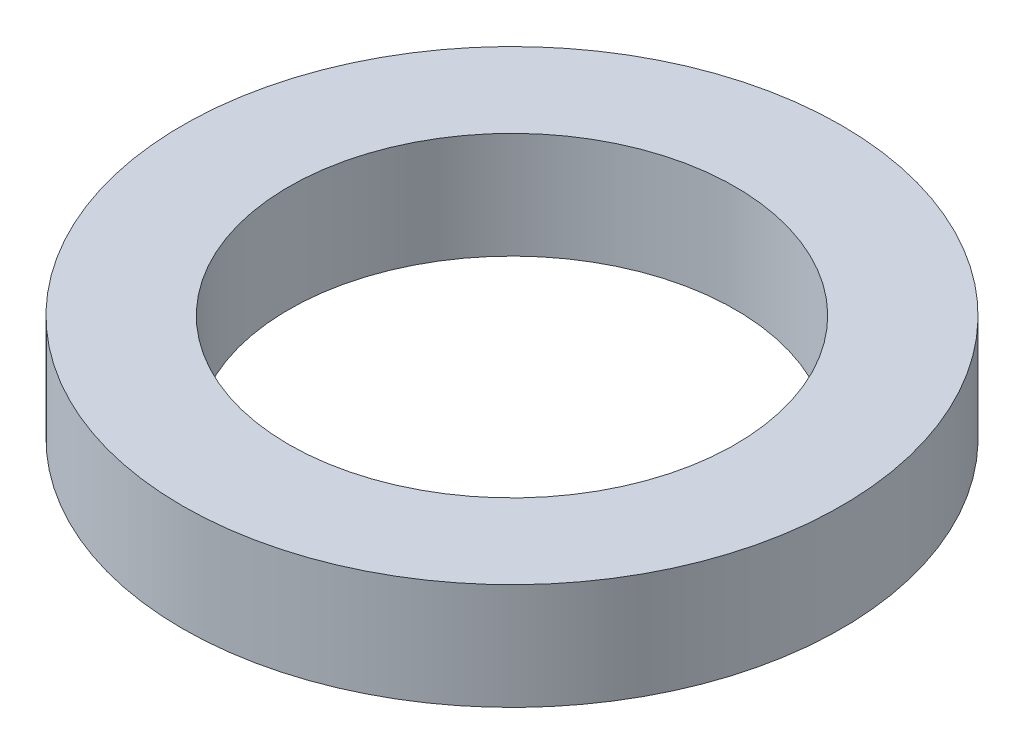
SolidWorks part; units mm, degrees
ref_plane "Front Plane" through (0, 0, 0) normal (0, 0, 1) x (1, 0, 0)
ref_plane "Top Plane" through (0, 0, 0) normal (0, 1, 0) x (1, 0, 0)
ref_plane "Right Plane" through (0, 0, 0) normal (1, 0, 0) x (0, 0, -1)
sketch "Sketch1" plane through (0, 0, 0) normal (0, 1, 0) x (1, 0, 0)
  circle A0 centre (0, 0) radius 2.1
  circle A1 centre (0, 0) radius 3.1
  dimension "D1" = 6.2
  dimension "D2" = 4.2
extrude "Boss-Extrude1" add sketch "Sketch1" along normal blind 1
equation "\"ID\"= 4.2"
equation "\"D2@Sketch1\"=\"ID\""
equation "\"thicc\" = 1"
equation "\"D1@Boss-Extrude1\"=\"thicc\""
